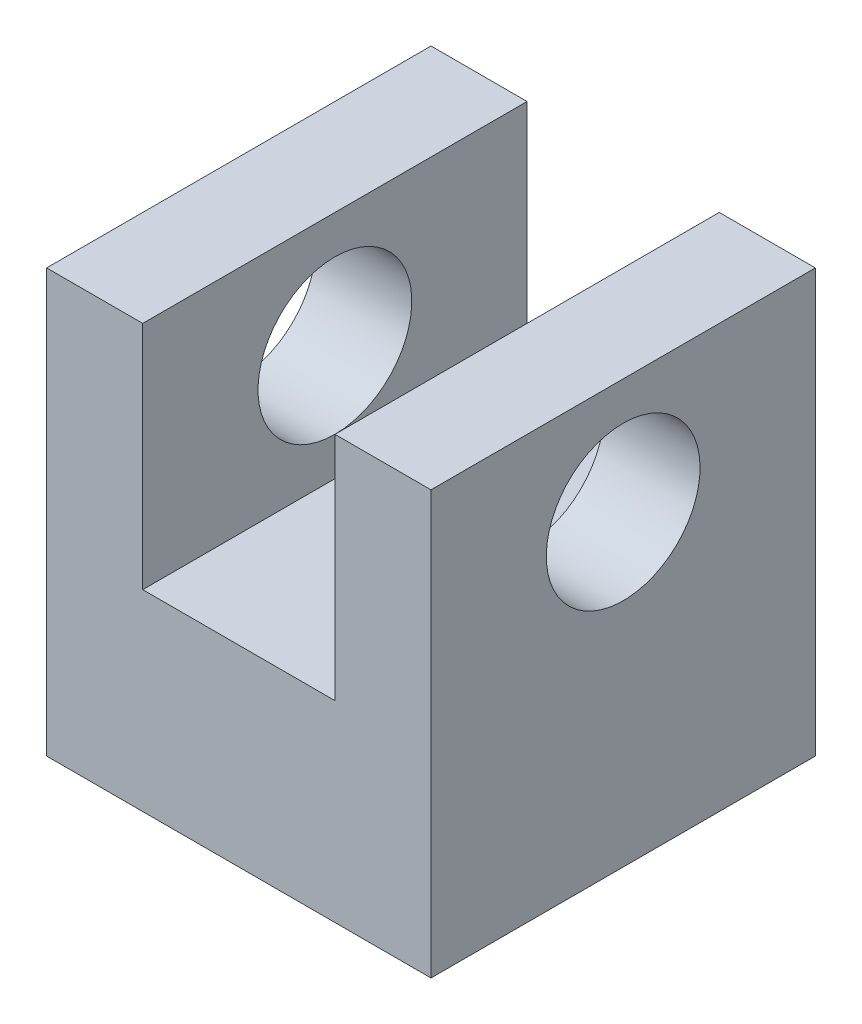
SolidWorks part; units mm, degrees
ref_plane "Front" through (0, 0, 0) normal (0, 0, 1) x (1, 0, 0)
ref_plane "Top" through (0, 0, 0) normal (0, 1, 0) x (1, 0, 0)
ref_plane "Right" through (0, 0, 0) normal (1, 0, 0) x (0, 0, -1)
sketch "Esquisse1" plane through (0, 0, 0) normal (0, 0, 1) x (1, 0, 0)
  line L0 (-10, 0) -> (10, 0)
  line L1 (10, 0) -> (10, 22)
  line L2 (10, 22) -> (5, 22)
  line L3 (5, 22) -> (5, 10)
  line L4 (5, 10) -> (-5, 10)
  line L5 (0, 0) -> (0, 10) construction
  line L6 (-5, 22) -> (-5, 10)
  line L7 (-10, 22) -> (-5, 22)
  line L8 (-10, 0) -> (-10, 22)
  dimension "D1" = 10
  dimension "D2" = 10
  dimension "D3" = 5
  dimension "D4" = 12
extrude "Boss.-Extru.1" add sketch "Esquisse1" along normal blind 20
sketch "Esquisse2" plane through (-5, 0, 0) normal (1, 0, 0) x (0, 0, -1)
  line L0 (-10, 10) -> (-10, 22) construction
  line L1 (-20, 10) -> (0, 10) construction
  line L2 (-20, 22) -> (0, 22) construction
  circle A0 centre (-10, 16) radius 4
  dimension "D1" = 8
extrude "Enlèv. mat.-Extru.1" cut sketch "Esquisse2" against normal through all both and the other way through all
